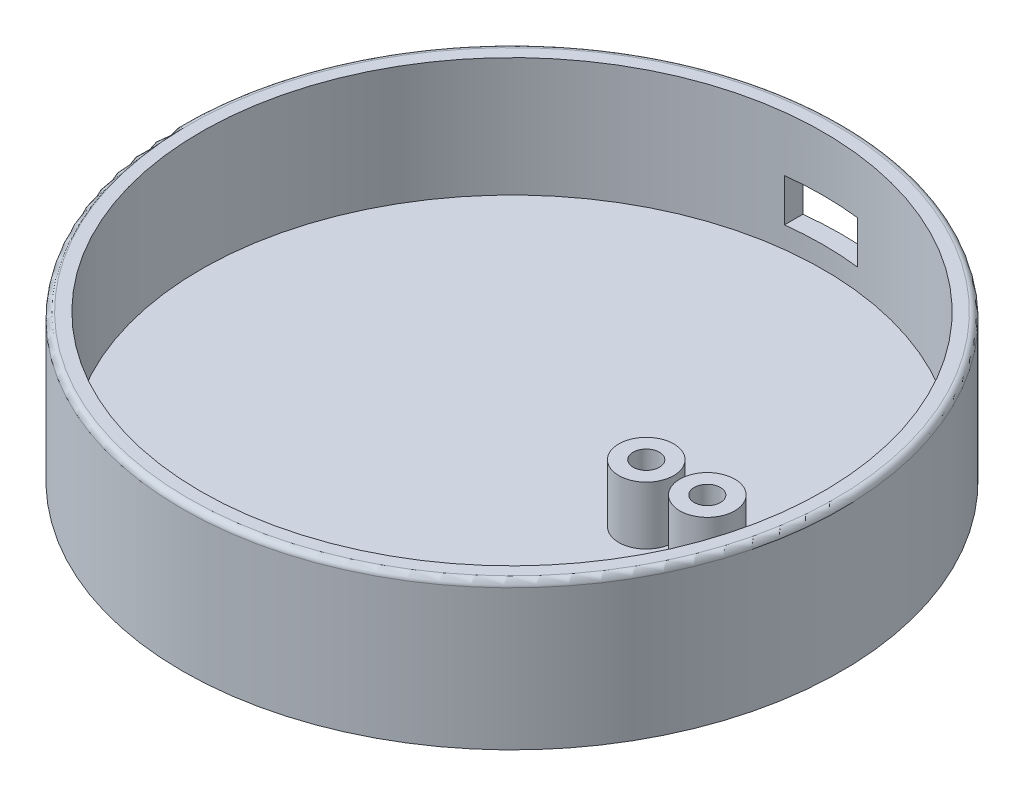
SolidWorks part; units mm, degrees
ref_plane "前视基准面" through (0, 0, 0) normal (0, 0, 1) x (1, 0, 0)
ref_plane "上视基准面" through (0, 0, 0) normal (0, 1, 0) x (1, 0, 0)
ref_plane "右视基准面" through (0, 0, 0) normal (1, 0, 0) x (0, 0, -1)
other "Configuration Table"
sketch "草图1" plane through (0, 0, 0) normal (0, 1, 0) x (1, 0, 0)
  circle A0 centre (0, 0) radius 54
extrude "Floor_D108_T4p5" add sketch "草图1" along normal blind 4.5
sketch "草图2" plane through (0, 0, 0) normal (0, 1, 0) x (1, 0, 0)
  circle A0 centre (0, 0) radius 54
  circle A1 centre (0, 0) radius 51
extrude "Rim_OD108_ID102_H24" add sketch "草图2" along normal blind 24
sketch "草图3" plane through (0, 0, 0) normal (0, 1, 0) x (1, 0, 0)
  circle A0 centre (22, 0) radius 4.5
  circle A1 centre (32, 0) radius 4.5
extrude "Sensor_fixed_posts" add sketch "草图3" along normal blind 14
sketch "草图4" plane through (0, 0, 0) normal (0, 1, 0) x (1, 0, 0)
  circle A0 centre (22, 0) radius 2.15
  circle A1 centre (32, 0) radius 2.15
extrude "M4_fixed_mount_clearance" cut sketch "草图4" along normal blind 14
sketch "草图5" plane through (0, 0, 0) normal (0, 1, 0) x (1, 0, 0)
  circle A0 centre (22, 0) radius 4.5
  circle A1 centre (32, 0) radius 4.5
extrude "M4_fixed_head_recess_D8p2_T2p7" cut sketch "草图5" along normal blind 2.7
ref_plane "基准面1" through (0, 8, 0) normal (0, 1, 0) x (1, 0, 0)
sketch "草图6" plane through (0, 8, 0) normal (0, 1, 0) x (1, 0, 0)
  line L1 (-6, 49) -> (6, 49)
  line L2 (-6, 49) -> (-6, 60)
  line L3 (-6, 60) -> (6, 60)
  line L4 (6, 49) -> (6, 60)
extrude "USB_C_side_opening_12x7" cut sketch "草图6" along normal blind 7
fillet "Base_outer_round_R1" radius 1 1 edges at (0, 24, 54)
